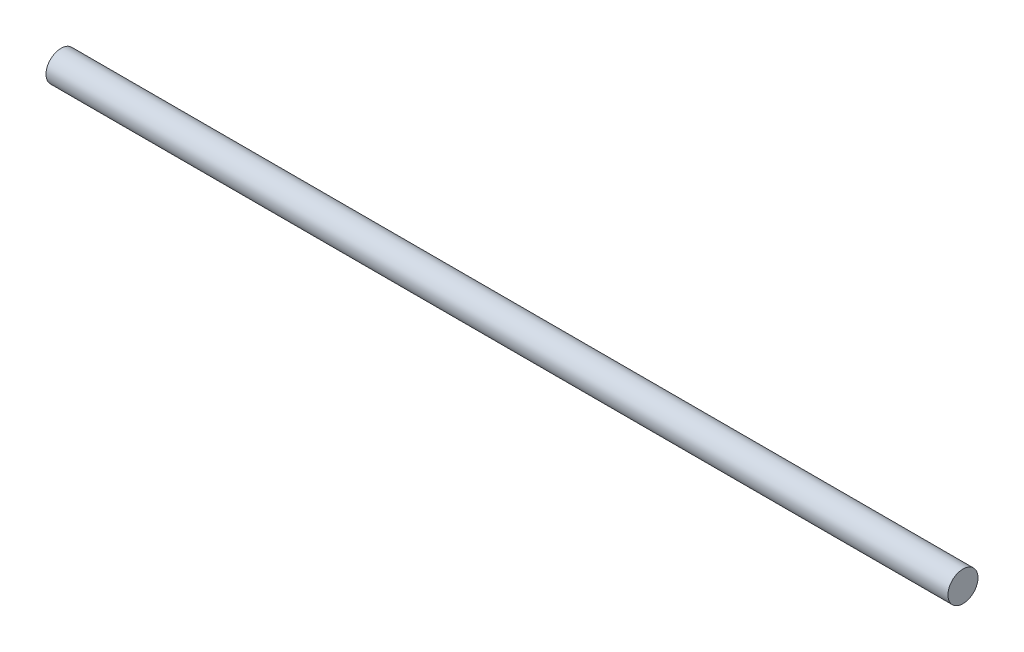
SolidWorks part; units mm, degrees
ref_plane "前视基准面" through (0, 0, 0) normal (0, 0, 1) x (1, 0, 0)
ref_plane "上视基准面" through (0, 0, 0) normal (0, 1, 0) x (1, 0, 0)
ref_plane "右视基准面" through (0, 0, 0) normal (1, 0, 0) x (0, 0, -1)
sketch "草图1" plane through (0, 0, 0) normal (0, 0, 1) x (1, 0, 0)
  line L1 (-50, 0) -> (50, 0)
  line L2 (-50, 0) -> (-50, 2)
  line L3 (-50, 2) -> (50, 2)
  line L4 (50, 0) -> (50, 2)
  dimension "D1" = 2
  dimension "D2" = 100
revolve "旋转1" add sketch "草图1" angle 360 about L1
cosmetic thread "装饰螺纹线1" parameters "D2"=3.242
sketch "Sketch1" plane through (50, 0, 0) normal (1, 0, 0) x (0, 0, -1)
  circle A1 centre (0, 0) radius 2
  circle A2 centre (0, 0) radius 2
  dimension "D1" = 0
extrude "Boss-Extrude1" add sketch "Sketch1" along normal blind 20
